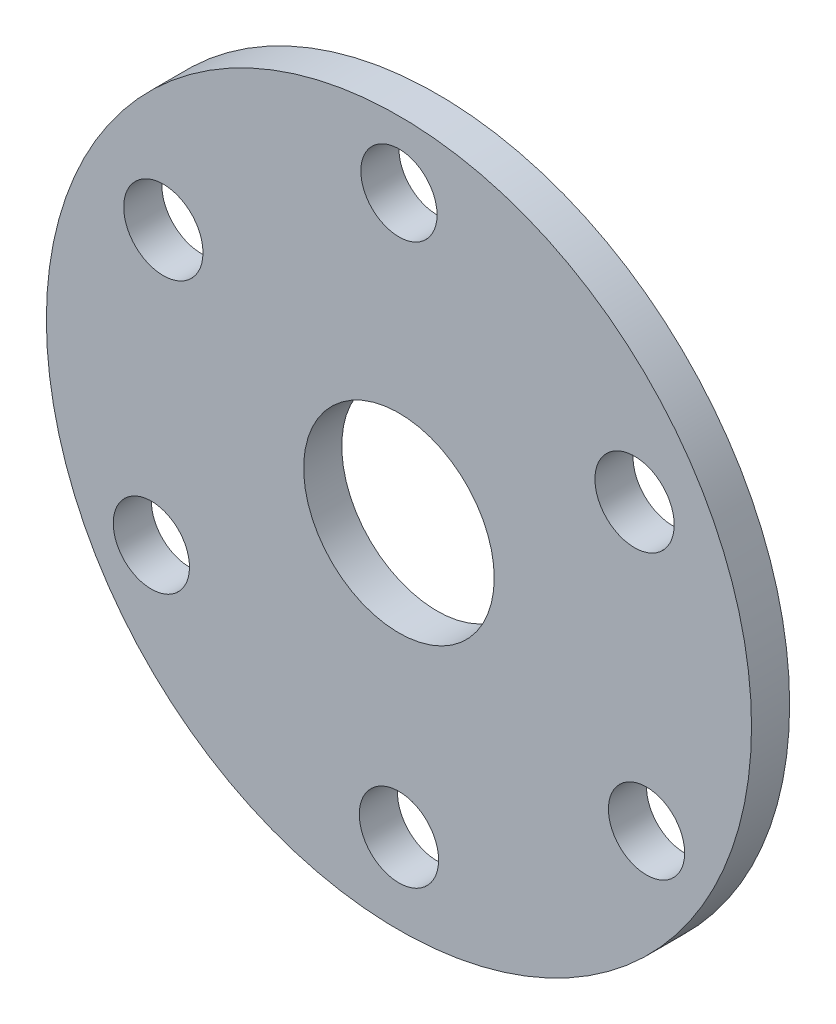
SolidWorks part; units mm, degrees
ref_plane "前视基准面" through (0, 0, 0) normal (0, 0, 1) x (1, 0, 0)
ref_plane "上视基准面" through (0, 0, 0) normal (0, 1, 0) x (1, 0, 0)
ref_plane "右视基准面" through (0, 0, 0) normal (1, 0, 0) x (0, 0, -1)
sketch "草图1" plane through (0, 0, 0) normal (0, 0, 1) x (1, 0, 0)
  line L0 (0, 0) -> (-12.9904, -7.5) construction
  line L1 (0, 0) -> (-17.5349, 10.1238) construction
  circle A0 centre (0, 0) radius 5
  circle A1 centre (0, 0) radius 15 construction
  circle A2 centre (0, 0) radius 14.25 construction
  circle A3 centre (0, 15) radius 2
  circle A4 centre (12.9904, -7.5) radius 2
  circle A5 centre (-12.9904, -7.5) radius 2
  circle A6 centre (-12.3626, 7.1375) radius 2.08
  circle A7 centre (12.3626, 7.1375) radius 2.08
  circle A8 centre (0, -14.2751) radius 2.08
  circle A9 centre (0, 0) radius 18.5
  dimension "D1" = 3
  dimension "D3" = 3
  dimension "D2" = 60
extrude "凸台-拉伸1" add sketch "草图1" along normal blind 2 contours A9
sketch "草图2" plane through (0, 0, 2) normal (0, 0, 1) x (1, 0, 0)
  line L0 (0, 0) -> (0, 5)
  line L1 (0, 0) -> (-5, 0)
  line L2 (0, 0) -> (-12.3626, 7.1375)
  line L3 (0, 0) -> (-5.989, -10.3733)
  circle A0 centre (0, 0) radius 5 construction
  dimension "D1" = 90
